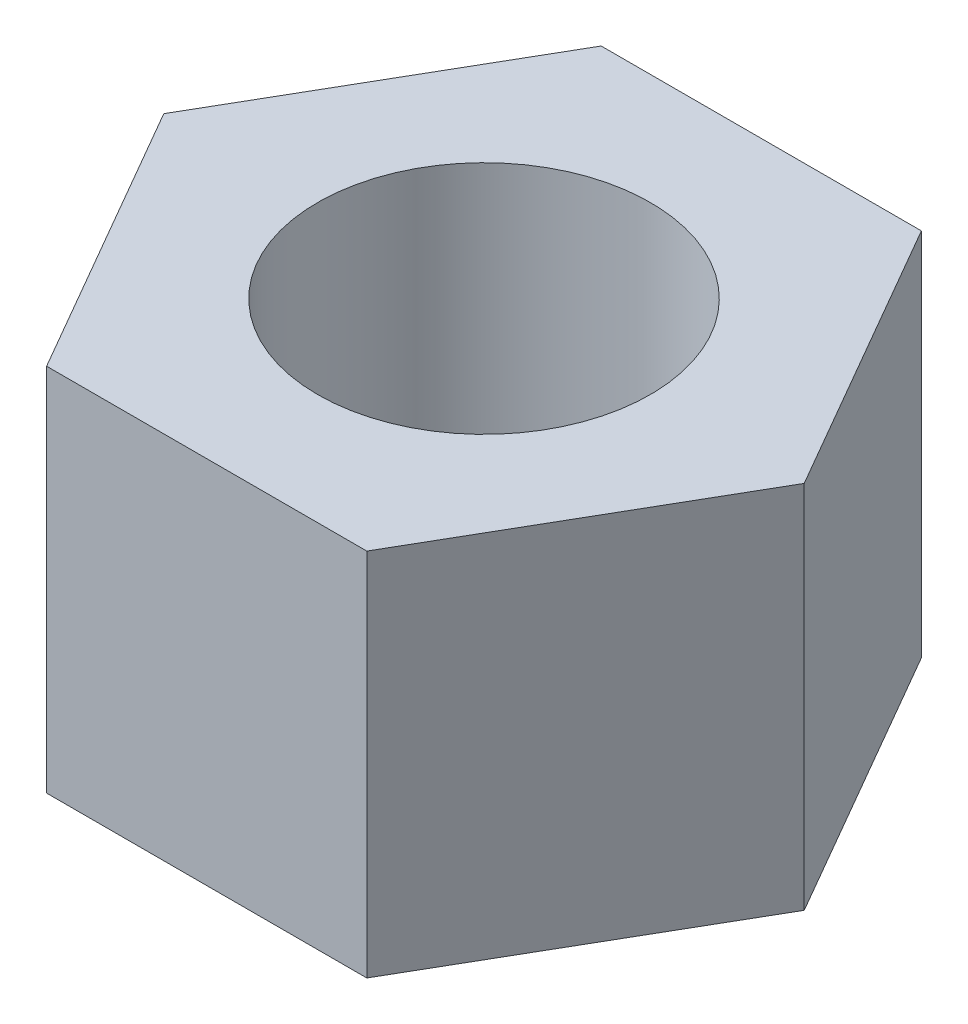
SolidWorks part; units mm, degrees
ref_plane "Front Plane" through (0, 0, 0) normal (0, 0, 1) x (1, 0, 0)
ref_plane "Top Plane" through (0, 0, 0) normal (0, 1, 0) x (1, 0, 0)
ref_plane "Right Plane" through (0, 0, 0) normal (1, 0, 0) x (0, 0, -1)
sketch "Sketch1" plane through (0, 0, 0) normal (0, 1, 0) x (1, 0, 0)
  line L1 (1.299, 2.25) -> (-1.299, 2.25)
  line L2 (-1.299, 2.25) -> (-2.5981, 0)
  line L3 (-2.5981, 0) -> (-1.299, -2.25)
  line L4 (-1.299, -2.25) -> (1.299, -2.25)
  line L5 (1.299, -2.25) -> (2.5981, 0)
  line L6 (2.5981, 0) -> (1.299, 2.25)
  circle A0 centre (0, 0) radius 2.25 construction
  circle A1 centre (0, 0) radius 1.35
  dimension "D2" = 2.7
  dimension "D1" = 4.5
extrude "Boss-Extrude1" add sketch "Sketch1" along normal mid plane 3
